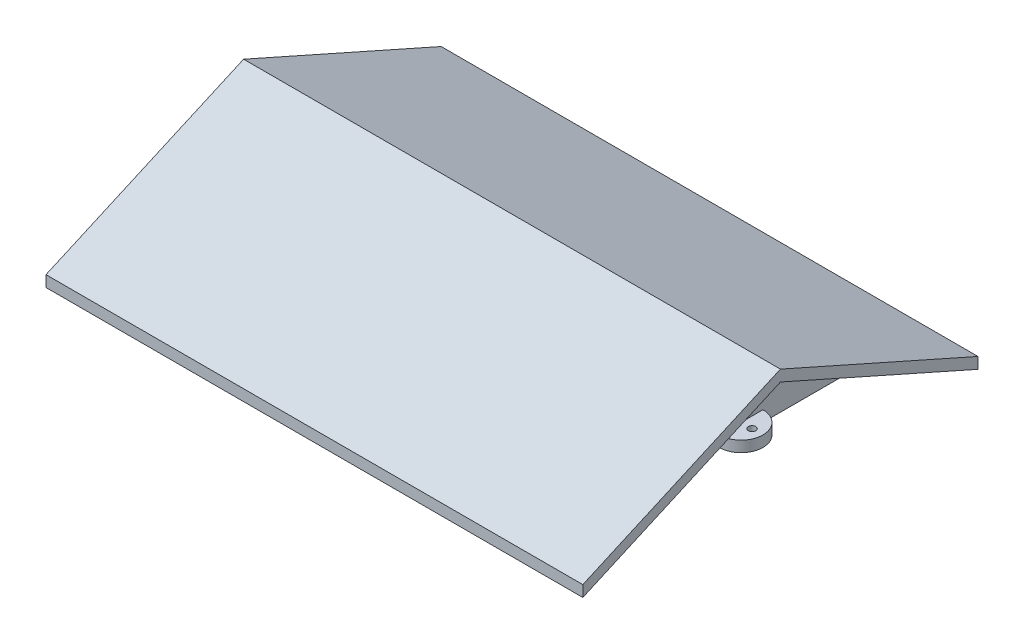
SolidWorks part; units mm, degrees
ref_plane "Front Plane" through (0, 0, 0) normal (0, 0, 1) x (1, 0, 0)
ref_plane "Top Plane" through (0, 0, 0) normal (0, 1, 0) x (1, 0, 0)
ref_plane "Right Plane" through (0, 0, 0) normal (1, 0, 0) x (0, 0, -1)
sketch "Sketch1" plane through (0, 0, 0) normal (1, 0, 0) x (0, 0, -1)
  line L0 (0, 0) -> (135, 0)
  line L1 (67.5, 0) -> (67.5, 30)
  line L2 (67.5, 30) -> (135, 0)
  line L3 (135, 0) -> (158.0421, -10.2409)
  line L4 (158.0421, -10.2409) -> (158.0421, -5.1205)
  line L5 (158.0421, -5.1205) -> (67.5, 35.1205)
  line L6 (67.5, 30) -> (0, 0)
  line L7 (0, 0) -> (-23.0421, -10.2409)
  line L8 (-23.0421, -10.2409) -> (-23.0421, -5.1205)
  line L9 (-23.0421, -5.1205) -> (67.5, 35.1205)
extrude "Boss-Extrude1" add sketch "Sketch1" against normal blind 248 and the other way blind 0.0001 contours L9 L8 L7 L6 L2 L3 L4 L5
sketch "Sketch2" plane through (0.0001, 0, 0) normal (1, 0, 0) x (0, 0, -1)
  line L0 (0, 0) -> (135, 0)
  line L1 (67.5, 30) -> (158.0421, -10.2409) construction
  line L2 (135, 0) -> (67.5, 30)
  line L3 (67.5, 30) -> (0, 0)
extrude "Boss-Extrude2" add sketch "Sketch2" against normal blind 25
sketch "Sketch3" plane through (0.0001, 0, 0) normal (1, 0, 0) x (0, 0, -1)
  line L0 (0, 0) -> (135, 0)
  line L1 (135, 0) -> (67.5, 30)
  line L2 (67.5, 30) -> (0, 0)
extrude "Cut-Extrude1" cut sketch "Sketch3" against normal blind 20
sketch "Sketch4" plane through (-248, 0, 0) normal (-1, 0, 0) x (0, 0, 1)
  line L0 (-135, 0) -> (0, 0)
  line L1 (0, 0) -> (-67.5, 30)
  line L2 (-67.5, 30) -> (-135, 0)
extrude "Boss-Extrude3" add sketch "Sketch4" against normal blind 25
sketch "Sketch5" plane through (-248, 0, 0) normal (-1, 0, 0) x (0, 0, 1)
  line L0 (-135, 0) -> (0, 0)
  line L1 (0, 0) -> (-67.5, 29.5827)
  line L2 (-67.5, 29.5827) -> (-135, 0)
extrude "Cut-Extrude2" cut sketch "Sketch5" against normal blind 20
sketch "Sketch6" plane through (0, 0, 0) normal (0, -1, 0) x (-1, 0, 0)
  line L0 (228, 67.5) -> (242, 67.5)
  circle A0 centre (228, 67.5) radius 14
  circle A1 centre (235, 67.5) radius 1.7
  line M1 (228, 0) -> (228, 135)
  line M3 (223, 135) -> (223, 0)
extrude "Boss-Extrude4" add sketch "Sketch6" against normal blind 5 contours A1 L0 A0 M1 | A1 L0 A0 M1 | A0 M3 | A0 M1 M3
sketch "Sketch7" plane through (0, 0, 0) normal (0, -1, 0) x (-1, 0, 0)
  line L0 (19.9999, 67.5) -> (10, 67.5)
  circle A0 centre (19.9999, 67.5) radius 9.9999
  circle A1 centre (15, 67.5) radius 1.7
  line M1 (19.9999, 135) -> (19.9999, 0)
  line M3 (24.9999, 0) -> (24.9999, 135)
extrude "Boss-Extrude5" add sketch "Sketch7" against normal blind 5 contours A1 L0 A0 M1 | A1 L0 A0 M1 | A0 M1 M3 | A0 M3
sketch "Sketch8" plane through (-228, 0, 0) normal (-1, 0, 0) x (0, 0, 1)
  line L0 (-67.5, 5) -> (-67.5, 25)
  line L1 (-53.5, 5) -> (-81.5, 5) construction
  circle A0 centre (-67.5, 25) radius 1.5
extrude "Cut-Extrude3" cut sketch "Sketch8" against normal blind 10
sketch "Sketch9" plane through (-248, 0, 0) normal (-1, 0, 0) x (0, 0, 1)
  line L0 (23.0421, -5.1205) -> (93.0421, -5.1205)
  line L1 (93.0421, -5.1205) -> (93.0421, -10.2409)
  line L2 (93.0421, -10.2409) -> (23.0421, -10.2409)
  line L3 (23.0421, -10.2409) -> (23.0421, -5.1205)
extrude "Boss-Extrude7" add sketch "Sketch9" against normal blind 250
sketch "Sketch11" plane through (-248, 0, 0) normal (-1, 0, 0) x (0, 0, 1)
  line L0 (23.0421, -5.1205) -> (93.0421, -5.1205)
  line L1 (93.0421, -5.1205) -> (93.0421, -10.2409)
  line L2 (93.0421, -10.2409) -> (23.0421, -10.2409)
  line L3 (23.0421, -10.2409) -> (23.0421, -5.1205)
extrude "Cut-Extrude4" cut sketch "Sketch11" against normal blind 250
sketch "Sketch12" plane through (0.0001, 0, 0) normal (1, 0, 0) x (0, 0, -1)
  line L0 (-23.0421, -5.1205) -> (67.5, 35.1205)
  line L1 (67.5, 35.1205) -> (158.0421, -5.1205)
  line L2 (158.0421, -5.1205) -> (158.0421, -10.2409)
  line L3 (158.0421, -10.2409) -> (67.5, 30)
  line L4 (67.5, 30) -> (-23.0421, -10.2409)
  line L5 (-23.0421, -10.2409) -> (-23.0421, -5.1205)
extrude "Cut-Extrude5" cut sketch "Sketch12" against normal blind 2
